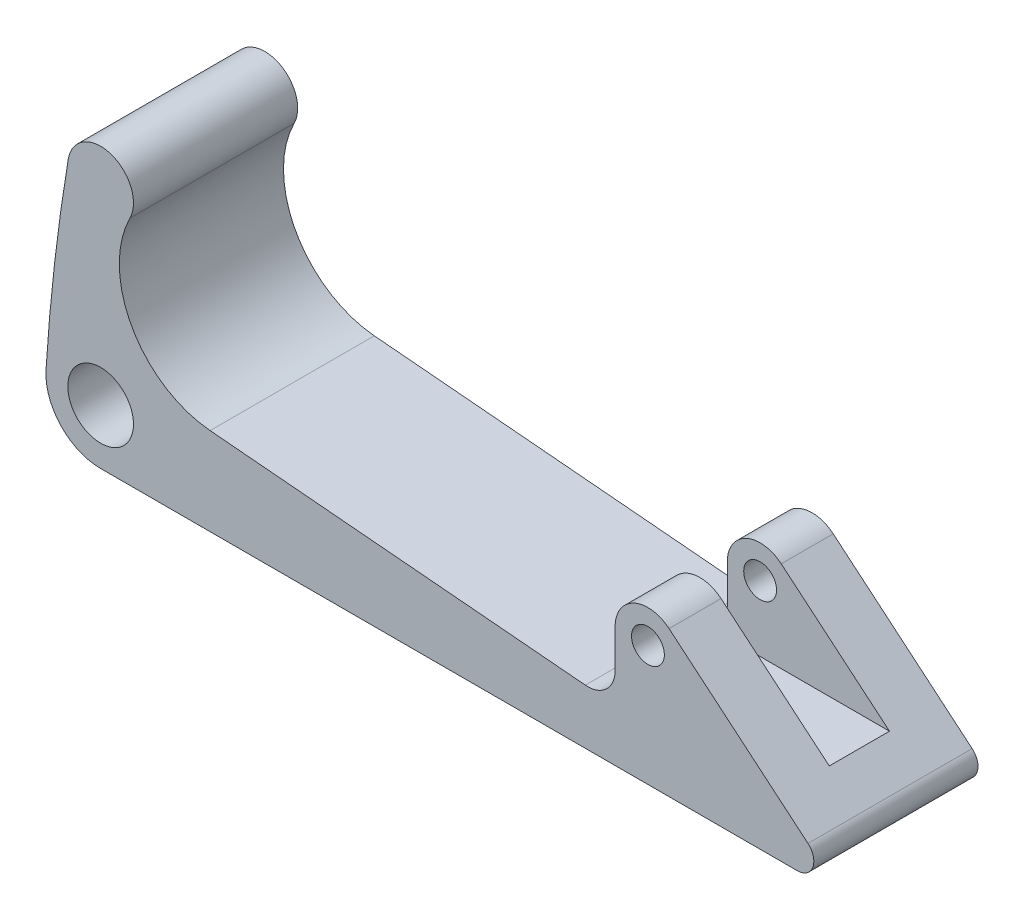
SolidWorks part; units mm, degrees
material "1.0060 (E335)"
ref_plane "Front Plane" through (0, 0, 0) normal (0, 0, 1) x (1, 0, 0)
ref_plane "Top Plane" through (0, 0, 0) normal (0, 1, 0) x (1, 0, 0)
ref_plane "Right Plane" through (0, 0, 0) normal (1, 0, 0) x (0, 0, -1)
sketch "Sketch1" plane through (0, 0, 0) normal (0, 0, 1) x (1, 0, 0)
  line L1 (0, -5) -> (63.6552, -5)
  line L2 (64.6194, -2.3509) -> (51.9284, 8.2981)
  line L3 (47, 6) -> (47, 2.4912)
  line L4 (44.2821, 0.0007) -> (10, 3)
  line L6 (10, 3) -> (10, -5) construction
  line L7 (78.2111, -2.9677) -> (49887.946, -4360.7548) construction
  circle A0 centre (0, 0) radius 3
  arc A1 (-2.9584, 17.998) -> (2.6783, 16.1484) centre (0, 17.5) cw
  arc A3 (63.6552, -5) -> (64.6194, -2.3509) centre (63.6552, -3.5) ccw
  arc A4 (51.9284, 8.2981) -> (47, 6) centre (50, 6) ccw
  arc A5 (47, 2.4912) -> (44.2821, 0.0007) centre (44.5, 2.4912) cw
  arc A6 (2.6783, 16.1484) -> (10, 3) centre (10.7921, 12.0538) ccw
  arc A8 (0, -5) -> (-4.9904, 0.3097) centre (0, 0) cw
  arc A9 (-4.9904, 0.3097) -> (-2.9584, 17.998) centre (164.6831, -10.2214) cw
  circle A10 centre (50, 6) radius 1.5
  point P4 (3, 17.5)
  point P20 (50, 9)
  point P21 (50, -0.4995)
  point P23 (65.1552, -3.5)
  point P28 (-5, 0)
  dimension "D1" = 50
  dimension "D2" = 1.5
  dimension "D3" = 3
  dimension "D4" = 2.5
  dimension "D5" = 6
  dimension "D10" = 170
  dimension "D11" = 3
  dimension "D12" = 5
  dimension "D17" = 3
  dimension "D6" = 17.5
  dimension "D7" = 40
  dimension "D8" = 8
  dimension "D9" = 5
  dimension "D13" = 14
  dimension "D14" = 40
  dimension "D15" = 4.5005
  dimension "D16" = 70.1552
extrude "Boss-Extrude1" add sketch "Sketch1" along normal mid plane 15
ref_plane "Plane1" through (0, 2.5, 0) normal (0, 1, 0) x (1, 0, 0)
sketch "Sketch2" plane through (0, 0, 0) normal (0, 1, 0) x (1, 0, 0)
  line L1 (44.2821, 2.75) -> (64.6194, 2.75)
  line L2 (44.2821, 2.75) -> (44.2821, -2.75)
  line L3 (44.2821, -2.75) -> (64.6194, -2.75)
  line L4 (64.6194, 2.75) -> (64.6194, -2.75)
  line L5 (64.6194, -7.5) -> (64.6194, 7.5) construction
  line L6 (44.2821, -7.5) -> (44.2821, 7.5) construction
  point P6 (47, 0)
  dimension "D1" = 5.5
extrude "Cut-Extrude1" cut sketch "Sketch2" along normal up to next contours L1 L4 L3 L2
